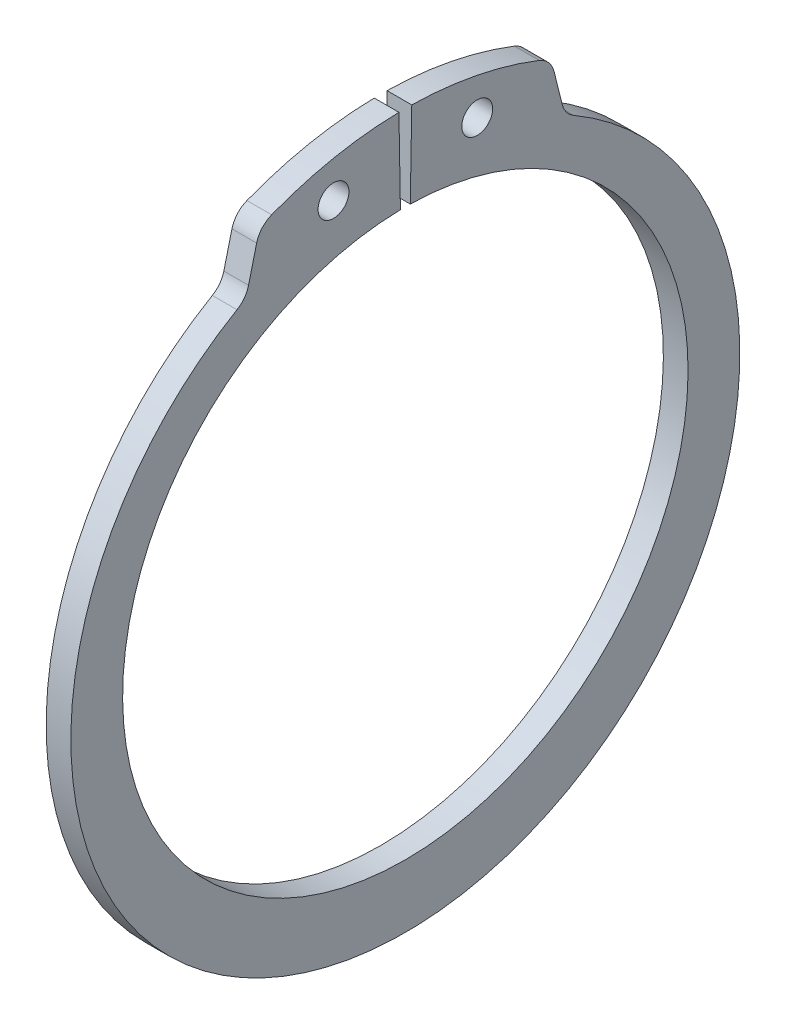
SolidWorks part; units mm, degrees
material "Plain Carbon Steel"
ref_plane "Front" through (0, 0, 0) normal (0, 0, 1) x (1, 0, 0)
ref_plane "Top" through (0, 0, 0) normal (0, 1, 0) x (1, 0, 0)
ref_plane "Right" through (0, 0, 0) normal (1, 0, 0) x (0, 0, -1)
sketch "Sketch1" plane through (0, 0, 0) normal (1, 0, 0) x (0, 0, -1)
  line L0 (0, 0) -> (0, 22.9) construction
  line L1 (-0.3997, 22.8965) -> (-0.5201, 29.7955)
  line L2 (-0.5201, 29.7955) -> (-11.2409, 29.6083) construction
  line L3 (-11.2409, 29.6083) -> (-12.9101, 22.9133) construction
  line L4 (0.5201, 29.7955) -> (0.3997, 22.8965)
  line L5 (0.5201, 29.7955) -> (11.2409, 29.6083) construction
  line L6 (11.2409, 29.6083) -> (12.9101, 22.9133) construction
  line L7 (-12.9101, 22.9133) -> (-11.2411, 19.9511) construction
  line L8 (12.9101, 22.9133) -> (11.2411, 19.9511) construction
  line L9 (0, -22.9) -> (0, -28) construction
  line L10 (-11.2409, 29.6083) -> (-0.3997, 22.8965) construction
  line L12 (0, 22.9) -> (0, 29.8) construction
  line L13 (11.8004, 27.364) -> (12.9101, 22.9133)
  line L14 (-11.8004, 27.364) -> (-12.9101, 22.9133)
  circle A0 centre (0, 0) radius 22.9 construction
  arc A1 (-0.3997, 22.8965) -> (0.3997, 22.8965) centre (0, 0) ccw
  circle A2 centre (0, -0.9065) radius 27.0935 construction
  circle A4 centre (-5.8203, 26.2524) radius 1.25
  circle A5 centre (5.8203, 26.2524) radius 1.25
  arc A6 (-12.9101, 22.9133) -> (12.9101, 22.9133) centre (0, -0.9065) ccw
  arc A7 (0.5201, 29.7955) -> (11.8004, 27.364) centre (0, 0) cw
  arc A8 (-0.5201, 29.7955) -> (-11.8004, 27.364) centre (0, 0) ccw
  dimension "A" = 45.8
  dimension "Hole" = 2.5
  dimension "Smin" = 3.4
  dimension "D1" = 75
  dimension "Angle" = 1
  dimension "H" = 6.9
extrude "Extrude1" add sketch "Sketch1" along normal mid plane 2
fillet "Fillet1" radius 2 4 edges at (0, 22.9133, 12.9101) (0, 27.364, 11.8004) (0, 27.364, -11.8004) (0, 22.9133, -12.9101)
sketch "Sketch2" plane through (0, 0, 0) normal (0, 0, 1) x (1, 0, 0)
  line L0 (-5.375, 0) -> (16.125, 0)
  line L1 (16.125, 0) -> (16.125, -25)
  line L2 (-5.375, 0) -> (-5.375, -23.5)
  line L3 (16.125, -25) -> (1.075, -25)
  line L4 (1.075, -25) -> (1.075, -23.5)
  line L5 (1.075, -23.5) -> (-1.075, -23.5)
  line L6 (-1.075, -23.5) -> (-1.075, -25)
  line L7 (-1.075, -25) -> (-5.375, -25) construction
  line L8 (-5.375, -25) -> (-5.375, 0) construction
  line L9 (0, -23.5) -> (0, 0) construction
  line L10 (16.125, 0) -> (14.0551, 0) construction
  line L11 (-5.375, -23.5) -> (-3.875, -25)
  line L12 (-3.875, -25) -> (-1.075, -25)
  dimension "D2" = 21.5
  dimension "D3" = 5.375
  dimension "D1" = 45
revolve "Revolve1" [suppressed] add sketch "Sketch2" angle 360 about L10
equation "\"D2@Sketch2\" = \"W@Sketch2\"*10"
equation "\"D3@Sketch2\" = \"D2@Sketch2\"/4"
equation "\"Smin@Sketch1\" = \"Smax@Sketch1\"/1.5"
equation "\"D1@Fillet1\" = \"D1@Extrude1\""
